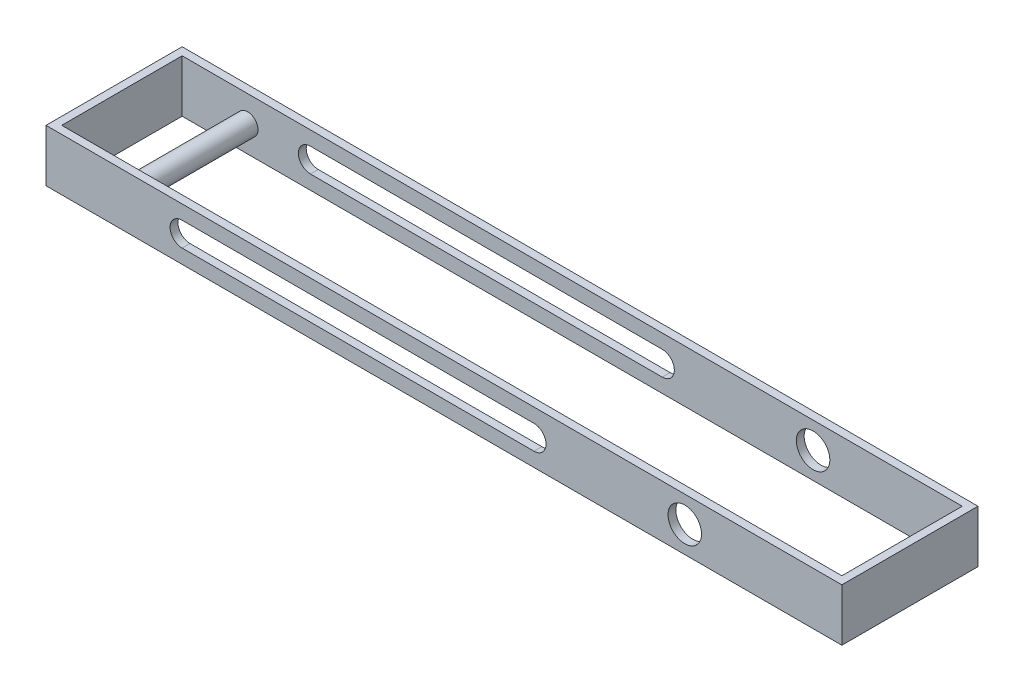
SolidWorks part; units mm, degrees
ref_plane "Front Plane" through (0, 0, 0) normal (0, 0, 1) x (1, 0, 0)
ref_plane "Top Plane" through (0, 0, 0) normal (0, 1, 0) x (1, 0, 0)
ref_plane "Right Plane" through (0, 0, 0) normal (1, 0, 0) x (0, 0, -1)
sketch "Sketch1" plane through (0, 0, 0) normal (0, 1, 0) x (1, 0, 0)
  line L1 (38, 6.5) -> (-38, 6.5)
  line L2 (38, 6.5) -> (38, -6.5)
  line L3 (38, -6.5) -> (-38, -6.5)
  line L4 (-38, 6.5) -> (-38, -6.5)
  line L5 (38, 6.5) -> (-38, -6.5) construction
  line L6 (38, -6.5) -> (-38, 6.5) construction
  line L7 (37.25, 5.75) -> (-37.25, 5.75)
  line L8 (37.25, 5.75) -> (37.25, -5.75)
  line L9 (37.25, -5.75) -> (-37.25, -5.75)
  line L10 (-37.25, 5.75) -> (-37.25, -5.75)
  line L11 (37.25, 5.75) -> (-37.25, -5.75) construction
  line L12 (37.25, -5.75) -> (-37.25, 5.75) construction
  point P0 (0, 0)
  point P6 (0, 0)
  dimension "D1" = 76
  dimension "D2" = 74.5
  dimension "D3" = 13
  dimension "D4" = 11.5
extrude "Boss-Extrude1" add sketch "Sketch1" along normal mid plane 5
sketch "Sketch2" plane through (0, 0, 6.5) normal (0, 0, 1) x (1, 0, 0)
  line L0 (-25, 0) -> (8.6, 0) construction
  line L1 (-25, 1.15) -> (8.6, 1.15)
  line L2 (-25, -1.15) -> (8.6, -1.15)
  line L3 (-38, 2.5) -> (-38, -2.5) construction
  circle A0 centre (23, 0) radius 1.6
  arc A1 (-25, 1.15) -> (-25, -1.15) centre (-25, 0) ccw
  arc A2 (8.6, -1.15) -> (8.6, 1.15) centre (8.6, 0) ccw
  point P5 (-8.2, 0)
  dimension "D2" = 1.15
  dimension "D4" = 3.2
  dimension "D1" = 13
  dimension "D3" = 46.6
  dimension "D5" = 61
extrude "Cut-Extrude1" cut sketch "Sketch2" against normal through all contours L2 A2 L1 A1
sketch "Sketch3" plane through (0, 0, -5.75) normal (0, 0, 1) x (1, 0, 0)
  line L0 (-38, 2.5) -> (-38, -2.5) construction
  circle A0 centre (-31, 0) radius 1
  dimension "D2" = 2
  dimension "D1" = 7
extrude "Boss-Extrude2" add sketch "Sketch3" along normal up to next contours A0
